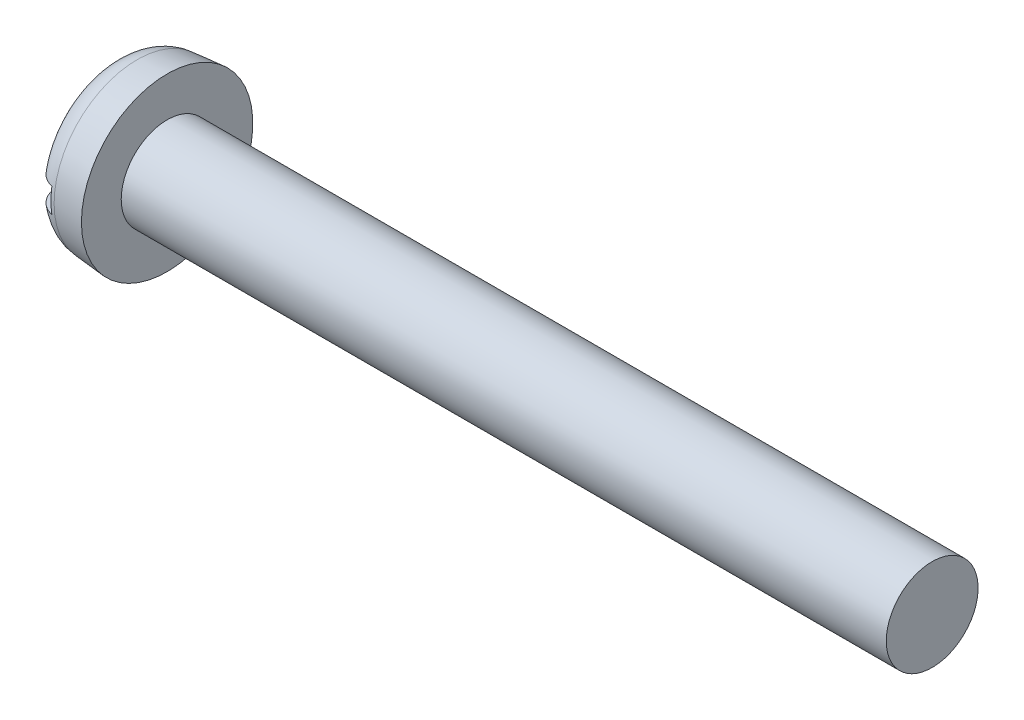
SolidWorks part; units mm, degrees
ref_plane "Plane1" through (0, 0, 0) normal (0, 0, 1) x (1, 0, 0)
ref_plane "Plane2" through (0, 0, 0) normal (0, 1, 0) x (1, 0, 0)
ref_plane "Plane3" through (0, 0, 0) normal (1, 0, 0) x (0, 0, -1)
sketch "BodySke" plane through (0, 0, 0) normal (0, 0, 1) x (1, 0, 0)
  line L0 (1.8, 1.5) -> (1.8, 2.8)
  line L1 (0, 0) -> (0, 2.6425)
  line L2 (-25.4, 0) -> (127, 0) construction
  line L3 (26.8, 0) -> (0, 0)
  line L4 (1.8, 1.5) -> (26.8, 1.5)
  line L5 (26.8, 1.5) -> (26.8, 0)
  line L6 (0, 2.6425) -> (1.8, 2.8)
  line L9 (2.3, 3.0875) -> (2.3, -6.4375) construction
  line L10 (1.8, 6.35) -> (1.8, -3.175) construction
  dimension "Head_ht" = 1.8
  dimension "Diameter" = 3
  dimension "Length" = 25
  dimension "Head_dia" = 5.6
  dimension "Advance" = 0.5
  dimension "Thread_nom" = 25
  dimension "Head_side_angle" = 5
revolve "Base-Revolve" add sketch "BodySke"
cosmetic thread "ThreadCosmetic" [suppressed]
fillet "Fillet1" [suppressed] radius 0.1
fillet "Fillet2" radius 0.9 1 edges at (0, 0, 2.6425)
sketch "Sketch2" plane through (0, 0, 0) normal (1, 0, 0) x (0, 0, -1)
  line L0 (2.8, -0.4) -> (-2.8, -0.4)
  line L1 (2.8, -0.4) -> (2.8, 0.4)
  line L2 (-2.8, 0.4) -> (2.8, 0.4)
  line L3 (-2.8, 0.4) -> (-2.8, -0.4)
  dimension "D1" = 5.6
  dimension "D2" = 2.8
  dimension "Slot_width" = 0.8
  dimension "D3" = 0.4
extrude "Slot" cut sketch "Sketch2" along normal blind 0.7
sketch "ThdSchSke" plane through (0, 0, 0) normal (0, 0, 1) x (1, 0, 0)
  line L0 (2.8, -1.2195) -> (2.6036, -1.5)
  line L1 (2.8, -1.2195) -> (2.9964, -1.5)
  line L2 (2.9964, -1.5) -> (2.9964, -1.875)
  line L3 (-3.175, 0) -> (5.1513, 0) construction
  line L5 (2.9964, -1.875) -> (2.6036, -1.875)
  line L6 (2.6036, -1.875) -> (2.6036, -1.5)
  dimension "Thread_minor" = 2.439
  dimension "Diameter" = 3
  dimension "Start" = 2.8
  dimension "SideAngle" = 55
  dimension "VeeAngle" = 70
  dimension "Overcut" = 3.75
revolve "ThreadSchematic" [suppressed] cut sketch "ThdSchSke" angle 360 about L3
pattern_linear "ThdSchPat" [suppressed]
equation "\"D1@Sketch2\" = \"Head_dia@BodySke\""
equation "\"D2@Sketch2\" = \"D1@Sketch2\" / 2"
equation "\"D3@Sketch2\" = \"Slot_width@Sketch2\" / 2"
equation "\"Thread_length@ThreadCosmetic\" = ((sgn( (\"Length@BodySke\" - \"Advance@BodySke\" * 2.0 ) - \"Thread_nom@BodySke\" )-1)*( (\"Length@BodySke\" - \"Advance@BodySke\"  * 2.0) - \"Thread_nom@BodySke\" ))/-2+ \"Thread_nom@BodySke\""
equation "\"Thread_minor@ThdSchSke\" = \"Thread_minor@ThreadCosmetic\""
equation "\"Diameter@ThdSchSke\" = \"Diameter@BodySke\""
equation "\"Overcut@ThdSchSke\" = \"Diameter@BodySke\" * 1.25"
equation "\"Start@ThdSchSke\" = \"Head_ht@BodySke\" + \"Length@BodySke\" - \"Thread_length@ThreadCosmetic\"  '---Non-countersunk---"
equation "\"Num_threads@ThdSchPat\" = int( \"Thread_length@ThreadCosmetic\" / \"Advance@BodySke\" + 0.999 )  + 1"
equation "\"Advance@ThdSchPat\" = \"Thread_length@ThreadCosmetic\" /  (\"Num_threads@ThdSchPat\" - 1) 'relax it"
